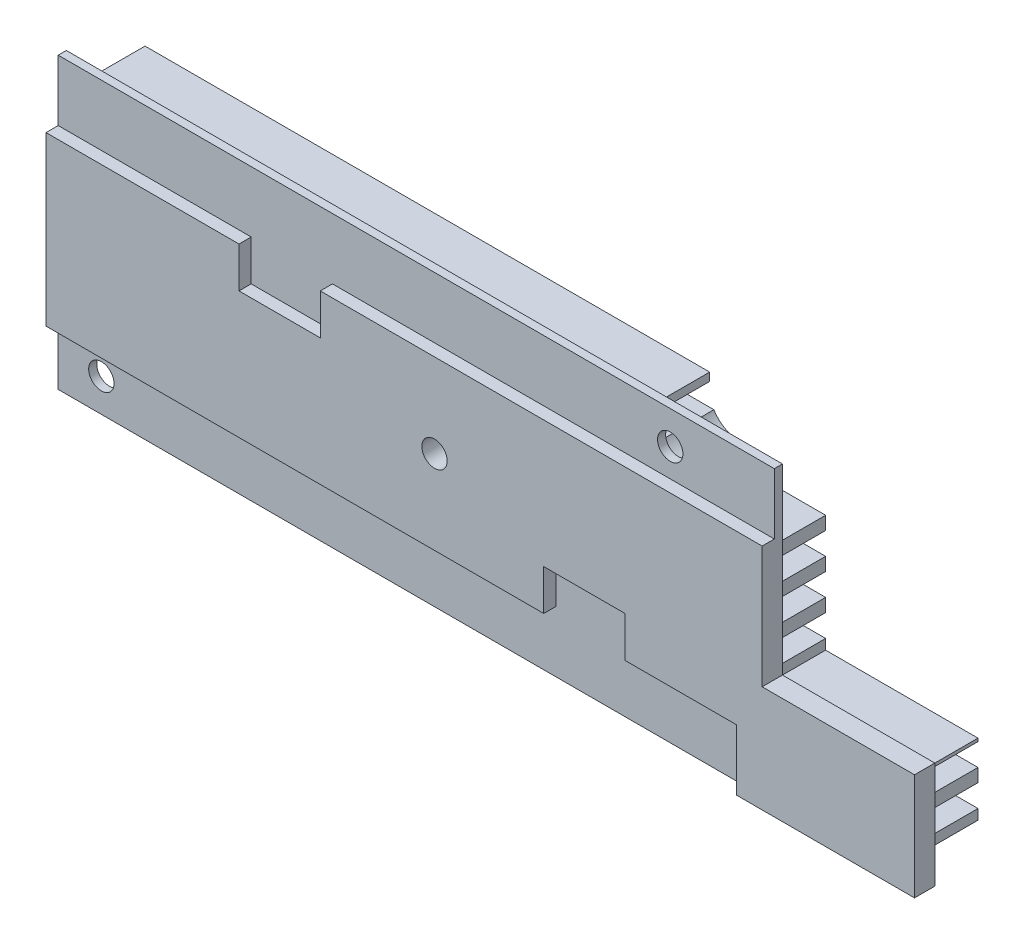
SolidWorks part; units mm, degrees
ref_plane "Plan de face" through (0, 0, 0) normal (0, 0, 1) x (1, 0, 0)
ref_plane "Plan de dessus" through (0, 0, 0) normal (0, 1, 0) x (1, 0, 0)
ref_plane "Plan de droite" through (0, 0, 0) normal (1, 0, 0) x (0, 0, -1)
sketch "Esquisse1" plane through (0, 0, 59.7018) normal (0, 0, -1) x (-1, 0, 0)
  line L0 (85.1853, 92.5076) -> (85.1853, 119.0076) construction
  line L1 (85.1853, 119.0076) -> (16.6853, 119.0076) construction
  line L2 (16.6853, 119.0076) -> (16.6853, 101.0076) construction
  line L3 (16.6853, 101.0076) -> (1.6853, 101.0076) construction
  line L4 (1.6853, 92.5076) -> (1.6853, 101.0076) construction
  line L5 (1.6853, 92.5076) -> (85.1853, 92.5076) construction
  line L6 (85.1853, 92.5076) -> (85.1853, 119.0076) construction
  line L7 (85.1853, 119.0076) -> (16.6853, 119.0076) construction
  line L8 (16.6853, 119.0076) -> (16.6853, 101.0076) construction
  line L9 (16.6853, 101.0076) -> (1.6853, 101.0076) construction
  line L10 (1.6853, 92.5076) -> (1.6853, 101.0076) construction
  line L11 (1.6853, 92.5076) -> (85.1853, 92.5076) construction
  line L12 (0.6853, 91.5076) -> (86.1853, 91.5076)
  line L13 (86.1853, 91.5076) -> (86.1853, 120.0076)
  line L14 (86.1853, 120.0076) -> (15.6853, 120.0076)
  line L15 (15.6853, 120.0076) -> (15.6853, 102.0076)
  line L16 (15.6853, 102.0076) -> (0.6853, 102.0076)
  line L17 (0.6853, 91.5076) -> (0.6853, 102.0076)
  dimension "D1" = 1
extrude "Boss.-Extru.1" add sketch "Esquisse1" along normal up to surface (2 mm away)
sketch "Esquisse2" plane through (0, 0, 57.7018) normal (0, 0, -1) x (-1, 0, 0)
  line L0 (84.4353, 93.2576) -> (84.4353, 118.2576)
  line L1 (84.4353, 118.2576) -> (17.4353, 118.2576)
  line L2 (17.4353, 118.2576) -> (17.4353, 100.2576)
  line L3 (17.4353, 100.2576) -> (2.4353, 100.2576)
  line L4 (2.4353, 100.2576) -> (2.4353, 93.2576)
  line L5 (2.4353, 93.2576) -> (84.4353, 93.2576)
  line L6 (15.6853, 102.0076) -> (0.6853, 102.0076)
  line L7 (0.6853, 102.0076) -> (0.6853, 91.5076)
  line L8 (0.6853, 91.5076) -> (86.1853, 91.5076)
  line L9 (86.1853, 91.5076) -> (86.1853, 120.0076)
  line L10 (86.1853, 120.0076) -> (15.6853, 120.0076)
  line L11 (15.6853, 120.0076) -> (15.6853, 102.0076)
  line L12 (15.6853, 102.0076) -> (0.6853, 102.0076) construction
  line L13 (0.6853, 102.0076) -> (0.6853, 91.5076) construction
  line L14 (0.6853, 91.5076) -> (86.1853, 91.5076) construction
  line L15 (86.1853, 91.5076) -> (86.1853, 120.0076) construction
  line L16 (86.1853, 120.0076) -> (15.6853, 120.0076) construction
  line L17 (15.6853, 120.0076) -> (15.6853, 102.0076) construction
  dimension "D1" = 0
  dimension "D2" = 1.75
extrude "Boss.-Extru.2" add sketch "Esquisse2" along normal blind 6
sketch "Esquisse3" plane through (0, 0, 51.7018) normal (0, 0, -1) x (-1, 0, 0)
  circle A0 centre (47.9353, 105.7576) radius 1.25 construction
  circle A1 centre (25.9353, 116.7576) radius 1.25 construction
  circle A2 centre (47.9353, 105.7576) radius 1.25
  circle A3 centre (25.9353, 116.7576) radius 1.25
  circle A4 centre (81.9353, 94.7576) radius 1.25 construction
  circle A5 centre (81.9353, 94.7576) radius 1.25
extrude "Enlèv. mat.-Extru.1" cut sketch "Esquisse3" against normal through all
sketch "Esquisse4" plane through (0, 0, 51.7018) normal (0, 0, -1) x (-1, 0, 0)
  line L0 (25.9353, 113.8421) -> (17.4353, 113.8421)
  line L1 (17.4353, 118.2576) -> (17.4353, 100.2576) construction
  line L2 (17.4353, 113.8421) -> (17.4353, 118.2576)
  line L3 (17.4353, 118.2576) -> (28.8507, 118.2576)
  line L4 (84.4353, 118.2576) -> (17.4353, 118.2576) construction
  line L5 (28.8507, 118.2576) -> (28.8507, 116.7576)
  line L6 (79.0198, 94.7576) -> (79.0198, 91.8421)
  line L7 (79.0198, 91.8421) -> (84.8507, 91.8421)
  line L8 (84.8507, 91.8421) -> (84.8507, 97.673)
  line L9 (84.8507, 97.673) -> (81.9353, 97.673)
  circle A0 centre (81.9353, 94.7576) radius 2.9155 construction
  circle A1 centre (47.9353, 105.7576) radius 2.9155
  circle A2 centre (25.9353, 116.7576) radius 2.9155 construction
  arc A3 (25.9353, 113.8421) -> (28.8507, 116.7576) centre (25.9353, 116.7576) ccw
  arc A4 (81.9353, 97.673) -> (79.0198, 94.7576) centre (81.9353, 94.7576) ccw
extrude "Enlèv. mat.-Extru.2" cut sketch "Esquisse4" against normal up to surface (6 mm away) up to face at (-34.7686, 103.9242, 57.7018)
sketch "Esquisse11" plane through (0, 0, 59.7018) normal (0, 0, 1) x (1, 0, 0)
  line L0 (-18.1853, 91.5076) -> (-18.1853, 97.5076)
  line L1 (-18.1853, 97.5076) -> (-29.1853, 97.5076)
  line L2 (-29.1853, 97.5076) -> (-29.1853, 101.5076)
  line L3 (-29.1853, 101.5076) -> (-37.1853, 101.5076)
  line L4 (-37.1853, 101.5076) -> (-37.1853, 97.5076)
  line L5 (-37.1853, 97.5076) -> (-86.1853, 97.5076)
  line L6 (-86.1853, 97.5076) -> (-86.1853, 91.5076)
  line L7 (-15.6853, 114.0076) -> (-59.1853, 114.0076)
  line L8 (-59.1853, 114.0076) -> (-59.1853, 110.0076)
  line L9 (-59.1853, 110.0076) -> (-67.1853, 110.0076)
  line L10 (-67.1853, 110.0076) -> (-67.1853, 114.0076)
  line L11 (-67.1853, 114.0076) -> (-86.1853, 114.0076)
  line L12 (-86.1853, 114.0076) -> (-86.1853, 120.0076)
  line L13 (-86.1853, 120.0076) -> (-15.6853, 120.0076)
  line L14 (-15.6853, 120.0076) -> (-15.6853, 114.0076)
  line L15 (-18.1853, 91.5076) -> (-86.1853, 91.5076)
  line L16 (-86.1853, 91.5076) -> (-86.1853, 120.0076) construction
  line L17 (-15.6853, 120.0076) -> (-15.6853, 102.0076) construction
  line L18 (-86.1853, 120.0076) -> (-15.6853, 120.0076) construction
  line L19 (-0.6853, 91.5076) -> (-86.1853, 91.5076) construction
  line L20 (-86.1853, 91.5076) -> (-86.1853, 120.0076) construction
  dimension "D1" = 6
  dimension "D2" = 6
  dimension "D3" = 6
  dimension "D4" = 6
  dimension "D5" = 68
  dimension "D6" = 10
  dimension "D7" = 10
  dimension "D8" = 8
  dimension "D9" = 8
  dimension "D10" = 11
  dimension "D11" = 19
extrude "Enlèv. mat.-Extru.3" cut sketch "Esquisse11" against normal blind 1.2
sketch "Esquisse12" plane through (0, 0, 51.7018) normal (0, 0, -1) x (-1, 0, 0)
  line L1 (86.1853, 96.4576) -> (0.6853, 96.4576)
  line L2 (86.1853, 96.4576) -> (86.1853, 94.2576)
  line L3 (86.1853, 94.2576) -> (0.6853, 94.2576)
  line L4 (0.6853, 96.4576) -> (0.6853, 94.2576)
  line L6 (2.4353, 93.2576) -> (79.0198, 93.2576) construction
  line L7 (86.1853, 97.7576) -> (0.6853, 97.7576)
  line L8 (86.1853, 99.9576) -> (0.6853, 99.9576)
  line L9 (86.1853, 99.9576) -> (86.1853, 97.7576)
  line L10 (0.6853, 99.9576) -> (0.6853, 97.7576)
  line L11 (86.1853, 101.2576) -> (0.6853, 101.2576)
  line L12 (86.1853, 103.4576) -> (0.6853, 103.4576)
  line L13 (86.1853, 103.4576) -> (86.1853, 101.2576)
  line L14 (0.6853, 103.4576) -> (0.6853, 101.2576)
  line L15 (86.1853, 104.7576) -> (0.6853, 104.7576)
  line L16 (86.1853, 106.9576) -> (0.6853, 106.9576)
  line L17 (86.1853, 106.9576) -> (86.1853, 104.7576)
  line L18 (0.6853, 106.9576) -> (0.6853, 104.7576)
  line L19 (86.1853, 108.2576) -> (0.6853, 108.2576)
  line L20 (86.1853, 110.4576) -> (0.6853, 110.4576)
  line L21 (86.1853, 110.4576) -> (86.1853, 108.2576)
  line L22 (0.6853, 110.4576) -> (0.6853, 108.2576)
  line L23 (86.1853, 111.7576) -> (0.6853, 111.7576)
  line L24 (86.1853, 113.9576) -> (0.6853, 113.9576)
  line L25 (86.1853, 113.9576) -> (86.1853, 111.7576)
  line L26 (0.6853, 113.9576) -> (0.6853, 111.7576)
  line L27 (86.1853, 115.2576) -> (0.6853, 115.2576)
  line L28 (86.1853, 117.4576) -> (0.6853, 117.4576)
  line L29 (86.1853, 117.4576) -> (86.1853, 115.2576)
  line L30 (0.6853, 117.4576) -> (0.6853, 115.2576)
  line L31 (86.1853, 91.5076) -> (86.1853, 120.0076) construction
  line L32 (0.6853, 102.0076) -> (0.6853, 91.5076) construction
  dimension "D1" = 1
  dimension "D2" = 2.2
  dimension "D3" = 7
extrude "Enlèv. mat.-Extru.4" cut sketch "Esquisse12" against normal up to surface (6 mm away) up to face at (-44.3519, 104.8409, 57.7018)
sketch "Esquisse13" plane through (0, 0, 51.7018) normal (0, 0, -1) x (-1, 0, 0)
  line L2 (84.8507, 97.673) -> (81.9353, 97.673) construction
  line L3 (79.0198, 94.7576) -> (79.0198, 91.8421) construction
  line L6 (86.1853, 97.673) -> (81.9353, 97.673)
  line L7 (79.0198, 94.7576) -> (79.0198, 91.5076)
  line L8 (0.6853, 91.5076) -> (86.1853, 91.5076) construction
  line L9 (79.0198, 91.5076) -> (86.1853, 91.5076)
  line L10 (86.1853, 91.5076) -> (86.1853, 120.0076) construction
  line L11 (86.1853, 91.5076) -> (86.1853, 97.673)
  arc A2 (81.9353, 97.673) -> (79.0198, 94.7576) centre (81.9353, 94.7576) ccw construction
  arc A3 (81.9353, 97.673) -> (79.0198, 94.7576) centre (81.9353, 94.7576) ccw
sketch "Esquisse14" plane through (0, 0, 51.7018) normal (0, 0, -1) x (-1, 0, 0)
  line L1 (28.8507, 118.2576) -> (28.8507, 116.7576) construction
  line L2 (25.9353, 113.8421) -> (17.4353, 113.8421) construction
  line L5 (28.8507, 120.0076) -> (28.8507, 116.7576)
  line L6 (25.9353, 113.8421) -> (15.6853, 113.8421)
  line L8 (15.6853, 120.0076) -> (15.6853, 102.0076) construction
  line L9 (15.6853, 120.0076) -> (15.6853, 113.8421)
  line L10 (86.1853, 120.0076) -> (15.6853, 120.0076) construction
  line L11 (28.8507, 120.0076) -> (15.6853, 120.0076)
  arc A0 (25.9353, 113.8421) -> (28.8507, 116.7576) centre (25.9353, 116.7576) ccw construction
  arc A1 (25.9353, 113.8421) -> (28.8507, 116.7576) centre (25.9353, 116.7576) ccw
sketch "Esquisse15" plane through (0, 0, 51.7018) normal (0, 0, -1) x (-1, 0, 0)
  line L0 (86.1853, 117.4576) -> (86.1853, 115.2576) construction
  line L1 (86.1853, 115.2576) -> (0.6853, 115.2576) construction
  line L2 (0.6853, 117.4576) -> (0.6853, 115.2576) construction
  line L3 (86.1853, 117.4576) -> (0.6853, 117.4576) construction
  line L4 (86.1853, 117.4576) -> (86.1853, 115.2576)
  line L5 (86.1853, 115.2576) -> (0.6853, 115.2576)
  line L6 (0.6853, 117.4576) -> (0.6853, 115.2576)
  line L7 (86.1853, 117.4576) -> (0.6853, 117.4576)
sketch "Esquisse16" plane through (0, 0, 51.7018) normal (0, 0, -1) x (-1, 0, 0)
  line L0 (86.1853, 113.9576) -> (0.6853, 113.9576) construction
  line L1 (0.6853, 113.9576) -> (0.6853, 111.7576) construction
  line L2 (86.1853, 111.7576) -> (0.6853, 111.7576) construction
  line L3 (86.1853, 113.9576) -> (86.1853, 111.7576) construction
  line L4 (86.1853, 113.9576) -> (0.6853, 113.9576)
  line L5 (0.6853, 113.9576) -> (0.6853, 111.7576)
  line L6 (86.1853, 111.7576) -> (0.6853, 111.7576)
  line L7 (86.1853, 113.9576) -> (86.1853, 111.7576)
sketch "Esquisse17" plane through (0, 0, 51.7018) normal (0, 0, -1) x (-1, 0, 0)
  line L0 (86.1853, 110.4576) -> (0.6853, 110.4576) construction
  line L1 (0.6853, 110.4576) -> (0.6853, 108.2576) construction
  line L2 (86.1853, 108.2576) -> (0.6853, 108.2576) construction
  line L3 (86.1853, 110.4576) -> (86.1853, 108.2576) construction
  line L4 (86.1853, 110.4576) -> (0.6853, 110.4576)
  line L5 (0.6853, 110.4576) -> (0.6853, 108.2576)
  line L6 (86.1853, 108.2576) -> (0.6853, 108.2576)
  line L7 (86.1853, 110.4576) -> (86.1853, 108.2576)
sketch "Esquisse18" plane through (0, 0, 51.7018) normal (0, 0, -1) x (-1, 0, 0)
  line L0 (86.1853, 106.9576) -> (0.6853, 106.9576) construction
  line L1 (0.6853, 106.9576) -> (0.6853, 104.7576) construction
  line L2 (86.1853, 104.7576) -> (0.6853, 104.7576) construction
  line L3 (86.1853, 106.9576) -> (86.1853, 104.7576) construction
  line L4 (86.1853, 106.9576) -> (0.6853, 106.9576)
  line L5 (0.6853, 106.9576) -> (0.6853, 104.7576)
  line L6 (86.1853, 104.7576) -> (0.6853, 104.7576)
  line L7 (86.1853, 106.9576) -> (86.1853, 104.7576)
sketch "Esquisse19" plane through (0, 0, 51.7018) normal (0, 0, -1) x (-1, 0, 0)
  line L0 (86.1853, 103.4576) -> (0.6853, 103.4576) construction
  line L1 (0.6853, 103.4576) -> (0.6853, 101.2576) construction
  line L2 (86.1853, 101.2576) -> (0.6853, 101.2576) construction
  line L3 (86.1853, 103.4576) -> (86.1853, 101.2576) construction
  line L4 (86.1853, 103.4576) -> (0.6853, 103.4576)
  line L5 (0.6853, 103.4576) -> (0.6853, 101.2576)
  line L6 (86.1853, 101.2576) -> (0.6853, 101.2576)
  line L7 (86.1853, 103.4576) -> (86.1853, 101.2576)
sketch "Esquisse20" plane through (0, 0, 51.7018) normal (0, 0, -1) x (-1, 0, 0)
  line L0 (86.1853, 99.9576) -> (0.6853, 99.9576) construction
  line L1 (0.6853, 99.9576) -> (0.6853, 97.7576) construction
  line L2 (86.1853, 97.7576) -> (0.6853, 97.7576) construction
  line L3 (86.1853, 99.9576) -> (86.1853, 97.7576) construction
  line L4 (86.1853, 99.9576) -> (0.6853, 99.9576)
  line L5 (0.6853, 99.9576) -> (0.6853, 97.7576)
  line L6 (86.1853, 97.7576) -> (0.6853, 97.7576)
  line L7 (86.1853, 99.9576) -> (86.1853, 97.7576)
sketch "Esquisse21" plane through (0, 0, 51.7018) normal (0, 0, -1) x (-1, 0, 0)
  line L0 (86.1853, 94.2576) -> (0.6853, 94.2576) construction
  line L1 (0.6853, 96.4576) -> (0.6853, 94.2576) construction
  line L2 (86.1853, 96.4576) -> (0.6853, 96.4576) construction
  line L3 (86.1853, 96.4576) -> (86.1853, 94.2576) construction
  line L4 (86.1853, 94.2576) -> (0.6853, 94.2576)
  line L5 (0.6853, 96.4576) -> (0.6853, 94.2576)
  line L6 (86.1853, 96.4576) -> (0.6853, 96.4576)
  line L7 (86.1853, 96.4576) -> (86.1853, 94.2576)
